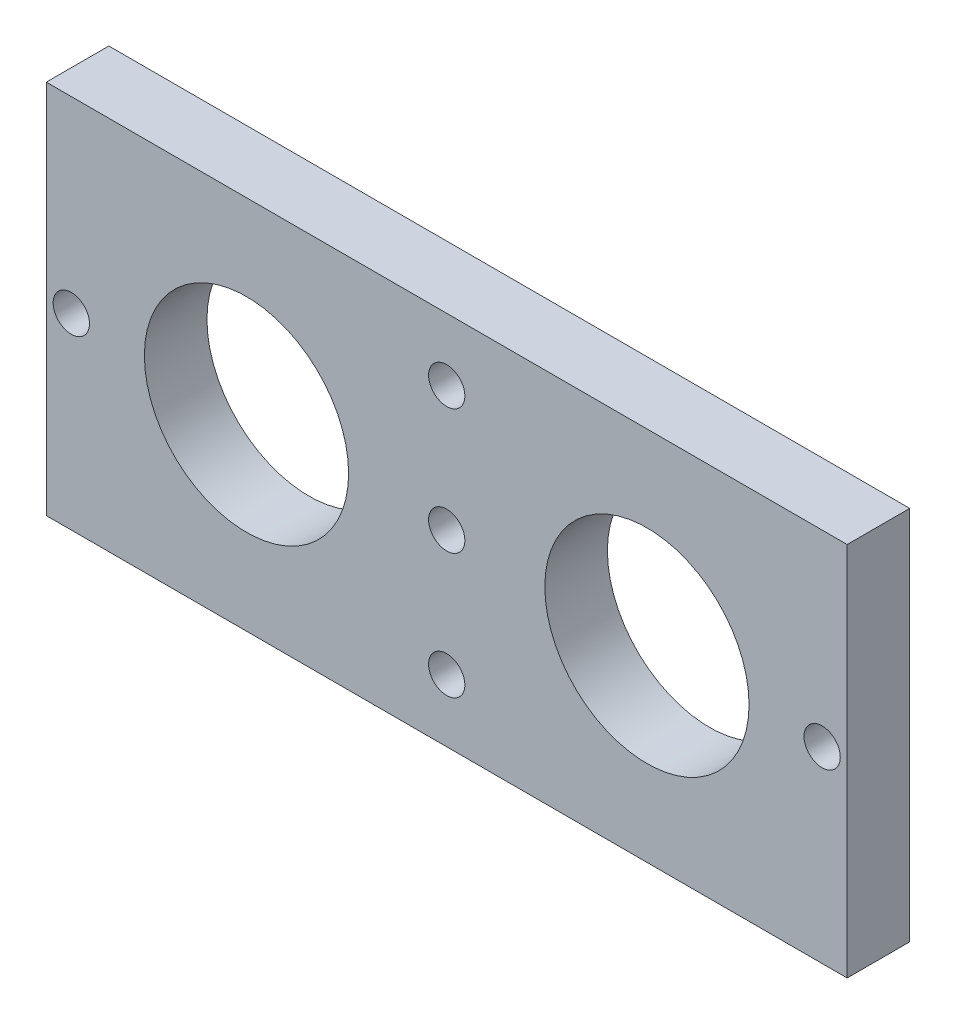
SolidWorks part; units mm, degrees
ref_plane "前视基准面" through (0, 0, 0) normal (0, 0, 1) x (1, 0, 0)
ref_plane "上视基准面" through (0, 0, 0) normal (0, 1, 0) x (1, 0, 0)
ref_plane "右视基准面" through (0, 0, 0) normal (1, 0, 0) x (0, 0, -1)
other "Configuration Table"
sketch "草图1" plane through (0, 0, 0) normal (0, 0, 1) x (1, 0, 0)
  line L0 (-6.8841, 5.4151) -> (25.1159, 5.4151) construction
  line L1 (-38.8841, 20.4151) -> (25.1159, 20.4151)
  line L2 (-38.8841, 20.4151) -> (-38.8841, -9.5849)
  line L3 (-38.8841, -9.5849) -> (25.1159, -9.5849)
  line L4 (25.1159, 20.4151) -> (25.1159, -9.5849)
  line L5 (-38.8841, 20.4151) -> (25.1159, -9.5849) construction
  line L6 (-38.8841, -9.5849) -> (25.1159, 20.4151) construction
  line L7 (-6.8841, 5.4151) -> (-38.8841, 5.4151) construction
  circle A0 centre (9.1159, 5.4151) radius 8.16
  circle A1 centre (-22.8841, 5.4151) radius 8.16
  point P0 (-6.8841, 5.4151)
  point P9 (9.1159, 5.4151)
  point P10 (-22.8841, 5.4151)
  point P11 (25.1159, 17.9151)
  point P15 (0, 0)
  point P16 (25.1159, 17.9151)
  dimension "D1" = 16.32
  dimension "D2" = 16.32
  dimension "D3" = 32
  dimension "D4" = 30
extrude "凸台-拉伸1" add sketch "草图1" along normal blind 5
sketch "草图2" plane through (0, 0, 5) normal (0, 0, 1) x (1, 0, 0)
  line L0 (-6.8841, 20.4151) -> (-6.8841, -9.5849) construction
  line L1 (25.1159, 20.4151) -> (-38.8841, 20.4151) construction
  line L2 (-38.8841, -9.5849) -> (25.1159, -9.5849) construction
  line L3 (-36.8841, 5.4151) -> (23.1159, 5.4151) construction
  circle A0 centre (-6.8841, 5.4151) radius 1.45
  circle A1 centre (23.1159, 5.4151) radius 1.45
  circle A2 centre (-36.8841, 5.4151) radius 1.45
  circle A3 centre (-6.8841, 15.4151) radius 1.45
  circle A5 centre (-6.8841, -4.5849) radius 1.45
  point P14 (-6.8841, 15.3349)
  point P19 (-6.8841, -4.8584)
  point P20 (-6.8841, 15.9459)
  point P23 (-6.6912, -4.6654)
  dimension "D1" = 2.9
  dimension "D4" = 2.9
  dimension "D5" = 2.9
  dimension "D2" = 30
  dimension "D3" = 30
  dimension "D6" = 20
  dimension "D7" = 10
extrude "切除-拉伸1" cut sketch "草图2" against normal blind 10
